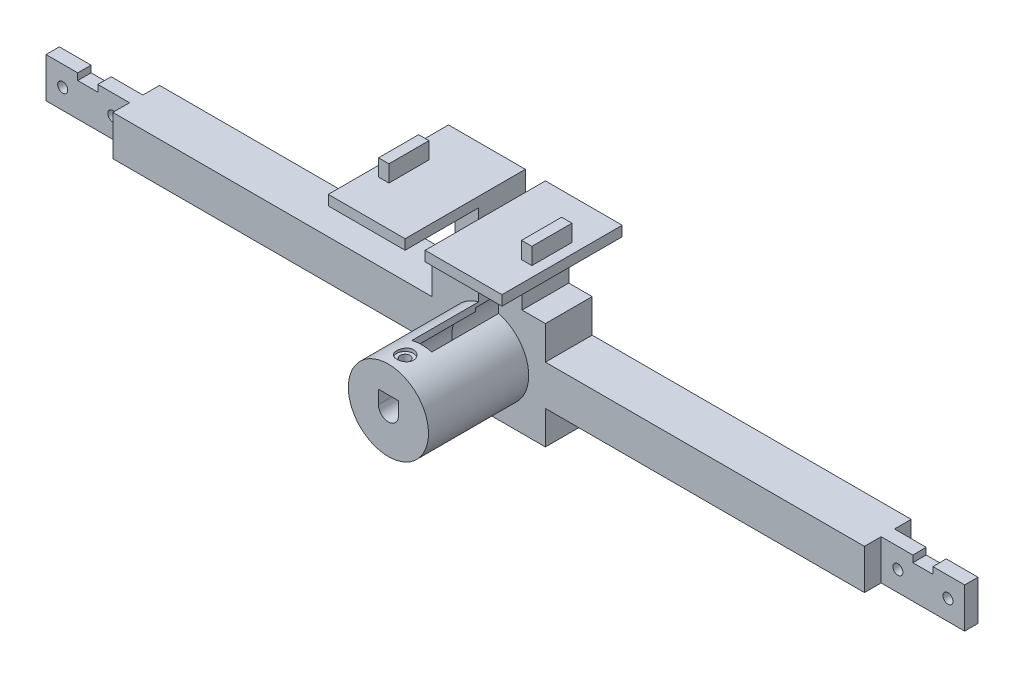
SolidWorks part; units mm, degrees
other "Markup1"
sketch "Sketch20" plane through (-137.5, 44, 54) normal (-0.9322, 0.081, 0.3528) x (0.3588, 0.0788, 0.9301)
material "PLA"
ref_plane "Front Plane" through (0, 0, 0) normal (0, 0, 1) x (1, 0, 0)
ref_plane "Top Plane" through (0, 0, 0) normal (0, 1, 0) x (1, 0, 0)
ref_plane "Right Plane" through (0, 0, 0) normal (1, 0, 0) x (0, 0, -1)
sketch "Sketch1" plane through (0, 0, 0) normal (0, 0, 1) x (1, 0, 0)
  line L0 (10, 16) -> (17, 16)
  line L1 (-17, -16) -> (17, -16)
  line L2 (-137.5, -6) -> (-137.5, 6)
  line L3 (-17, 16) -> (-10, 16)
  line L4 (137.5, -6) -> (137.5, 6)
  line L7 (-10, 36) -> (10, 36)
  line L8 (-10, 36) -> (-10, 16)
  line L10 (10, 36) -> (10, 16)
  line L11 (0, -55) -> (0, 55) construction
  line L14 (-137.5, 6) -> (-17, 6)
  line L15 (-17, 16) -> (-17, 6)
  line L16 (137.5, 6) -> (17, 6)
  line L17 (17, 16) -> (17, 6)
  line L20 (55, 0) -> (-55, 0) construction
  line L22 (17, -16) -> (17, -6)
  line L23 (137.5, -6) -> (17, -6)
  line L25 (-137.5, -6) -> (-17, -6)
  line L26 (-17, -16) -> (-17, -6)
  point P0 (0, 0)
  point P6 (0, 36)
  dimension "D1" = 275
  dimension "D2" = 12
  dimension "D3" = 20
  dimension "D4" = 20
  dimension "D5" = 7
  dimension "D6" = 10
extrude "Boss-Extrude1" add sketch "Sketch1" along normal blind 14 contours L3 L8 L7 L10 L0 L17 L16 L4 L23 L22 L1 L26 L25 L2 L14 L15
sketch "Sketch2" plane through (0, 0, 14) normal (0, 0, 1) x (1, 0, 0)
  circle A0 centre (0, 0) radius 12
  dimension "D1" = 24
extrude "Boss-Extrude2" add sketch "Sketch2" along normal blind 30 contours A0
sketch "Sketch5" plane through (0, 0, 0) normal (0, 0, -1) x (-1, 0, 0)
  line L2 (-3, 36) -> (-3, 10.583)
  line L4 (3, 36) -> (3, 10.583)
  line L6 (10, 36) -> (-10, 36) construction
  line L7 (-3, 36) -> (3, 36)
  arc A0 (-3, 10.583) -> (3, 10.583) centre (0, 0) ccw
  point P7 (0, 36)
  point P8 (0, 36)
  dimension "D1" = 22
  dimension "D2" = 6
extrude "Cut-Extrude2" cut sketch "Sketch5" against normal offset from surface (34 mm away) 10 contours A0 L4 L7 L2 up to face at (12, 0, 44)
sketch "Sketch7" plane through (0, 0, 34) normal (0, 0, -1) x (-1, 0, 0)
  line L0 (-3, 10.583) -> (-3, 9.5394)
  line L1 (3, 10.583) -> (3, 9.5394)
  arc A0 (-3, 9.5394) -> (3, 9.5394) centre (0, 0) ccw
  arc A1 (-3, 10.583) -> (3, 10.583) centre (0, 0) ccw construction
  arc A2 (-3, 10.583) -> (3, 10.583) centre (0, 0) ccw
  dimension "D1" = 1
extrude "Boss-Extrude3" add sketch "Sketch7" along normal offset from surface (19 mm away) 1 up to face at (0, 8.7809, 14)
sketch "Sketch6" plane through (0, 0, 44) normal (0, 0, 1) x (1, 0, 0)
  line L0 (-3, 0) -> (-3, 4)
  line L1 (-3, 4) -> (3, 4)
  line L2 (3, 4) -> (3, 0)
  arc A0 (-3, 0) -> (3, 0) centre (0, 0) ccw
  dimension "D1" = 6
  dimension "D2" = 4
extrude "Cut-Extrude3" cut sketch "Sketch6" against normal through all contours A0 L2 L1 L0
sketch "Sketch10" plane through (0, 4, 0) normal (0, -1, 0) x (-1, 0, 0)
  line L0 (-3, -44) -> (3, -34) construction
  circle A0 centre (0, -39) radius 1.5
  point P2 (0, -39)
  dimension "D1" = 3
extrude "Cut-Extrude5" cut sketch "Sketch10" against normal through all
sketch "Sketch11" plane through (0, 4, 0) normal (0, -1, 0) x (1, 0, 0)
  line L1 (2, 37.8453) -> (2, 40.1547)
  line L2 (2, 40.1547) -> (0, 41.3094)
  line L3 (0, 41.3094) -> (-2, 40.1547)
  line L4 (-2, 40.1547) -> (-2, 37.8453)
  line L5 (-2, 37.8453) -> (0, 36.6906)
  line L6 (0, 36.6906) -> (2, 37.8453)
  circle A0 centre (0, 39) radius 2 construction
  point P1 (1, 40.7321)
  dimension "D1" = 4
extrude "Cut-Extrude6" cut sketch "Sketch11" against normal blind 1.5
sketch "Sketch12" plane through (10, 0, 0) normal (1, 0, 0) x (0, 0, -1)
  line L0 (-14, 36) -> (0, 36) construction
  circle A0 centre (-7, 30.5) radius 1.5
  point P4 (-7, 36)
  dimension "D1" = 3
  dimension "D2" = 5.5
extrude "Cut-Extrude7" cut sketch "Sketch12" against normal up to surface (20 mm away) up to face at (-10, 26, 7)
sketch "Sketch13" plane through (10, 0, 0) normal (1, 0, 0) x (0, 0, -1)
  circle A0 centre (-7, 30.5) radius 2.5
  dimension "D1" = 5
extrude "Cut-Extrude8" cut sketch "Sketch13" against normal blind 1
sketch "Sketch14" plane through (-10, 0, 0) normal (-1, 0, 0) x (0, 0, 1)
  line L1 (4.6906, 30.5) -> (5.8453, 28.5)
  line L2 (5.8453, 28.5) -> (8.1547, 28.5)
  line L3 (8.1547, 28.5) -> (9.3094, 30.5)
  line L4 (9.3094, 30.5) -> (8.1547, 32.5)
  line L5 (8.1547, 32.5) -> (5.8453, 32.5)
  line L6 (5.8453, 32.5) -> (4.6906, 30.5)
  circle A0 centre (7, 30.5) radius 2 construction
  dimension "D1" = 4
extrude "Cut-Extrude9" cut sketch "Sketch14" against normal blind 1 contours L6 L1 L2 L3 L4 L5
sketch "Sketch15" plane through (0, 6, 0) normal (0, 1, 0) x (1, 0, 0)
  line L10 (-137.5, -14) -> (-112.5, -14)
  line L15 (-137.5, -14) -> (-137.5, -9)
  line L16 (-137.5, -9) -> (-112.5, -9)
  line L17 (-112.5, -14) -> (-112.5, -9)
  line L18 (-137.5, 0) -> (-112.5, 0)
  line L19 (-137.5, 0) -> (-137.5, -5)
  line L20 (-137.5, -5) -> (-112.5, -5)
  line L21 (-112.5, 0) -> (-112.5, -5)
  dimension "D1" = 25
  dimension "D2" = 5
  dimension "D3" = 5
  dimension "D4" = 25
extrude "Cut-Extrude11" cut sketch "Sketch15" against normal through all
mirror "Mirror2" about plane through (0, 0, 0) normal (1, 0, 0) of "Cut-Extrude11"
sketch "Sketch17" plane through (0, 5.5, 0) normal (0, -1, 0) x (1, 0, 0)
  circle A0 centre (0, 39) radius 2.5
  dimension "D1" = 5
extrude "Cut-Extrude12" cut sketch "Sketch17" against normal through all from offset 5.5 offset against normal yes
sketch "Sketch18" plane through (0, 36, 0) normal (0, 1, 0) x (1, 0, 0)
  line L0 (-17, 0) -> (-10, 0) construction
  line L1 (-26, 0) -> (-3, 0)
  line L2 (-26, 0) -> (-26, -36)
  line L3 (-26, -36) -> (-3, -36)
  line L4 (26, 0) -> (26, -36)
  line L5 (3, -14) -> (3, -34) construction
  line L7 (-3, 0) -> (-3, -36)
  line L9 (3, 0) -> (3, -36)
  line L10 (3, 0) -> (26, 0)
  line L11 (3, -36) -> (26, -36)
  dimension "D1" = 36
  dimension "D2" = 52
extrude "Boss-Extrude7" add sketch "Sketch18" along normal blind 3
sketch "Sketch19" plane through (0, 39, 0) normal (0, 1, 0) x (1, 0, 0)
  line L0 (-26, 0) -> (-26, -36) construction
  line L1 (-22.95, -12) -> (-19.85, -12)
  line L2 (-22.95, -12) -> (-22.95, -24)
  line L3 (-22.95, -24) -> (-19.85, -24)
  line L4 (-19.85, -12) -> (-19.85, -24)
  line L5 (-22.95, -12) -> (-19.85, -24) construction
  line L6 (-22.95, -24) -> (-19.85, -12) construction
  line L7 (0, -24.2) -> (0, 24.2) construction
  line L8 (22.95, -24) -> (19.85, -12) construction
  line L9 (22.95, -12) -> (19.85, -24) construction
  line L10 (19.85, -12) -> (19.85, -24)
  line L11 (22.95, -24) -> (19.85, -24)
  line L12 (22.95, -12) -> (22.95, -24)
  line L13 (22.95, -12) -> (19.85, -12)
  point P0 (-21.4, -18)
  point P7 (-26, -18)
  point P8 (-21.4, -24)
  point P16 (21.4, -18)
  dimension "D1" = 3.1
  dimension "D2" = 12
  dimension "D3" = 21.4
extrude "Boss-Extrude8" add sketch "Sketch19" along normal blind 5
sketch "Sketch21" plane through (0, 0, 9) normal (0, 0, 1) x (1, 0, 0)
  line L0 (-137.5, -6) -> (-137.5, 6) construction
  line L1 (-112.5, -6) -> (-112.5, 6) construction
  line L2 (-112.5, 6) -> (-137.5, 6) construction
  line L4 (-128, 6) -> (-128, 4)
  line L5 (-128, 4) -> (-122, 4)
  line L6 (-122, 6) -> (-122, 4)
  line L7 (-125, 6) -> (-122, 4) construction
  line L8 (-128, 4) -> (-125, 6) construction
  line L9 (-128, 6) -> (-122, 6)
  circle A0 centre (-132.5, 0) radius 1.5
  circle A1 centre (-117.5, 0) radius 1.5
  point P5 (-137.5, 0)
  point P10 (-125, 6)
  point P12 (-125, 6)
  dimension "D1" = 3
  dimension "D3" = 2
  dimension "D2" = 5
  dimension "D4" = 5
  dimension "D5" = 6
extrude "Cut-Extrude13" cut sketch "Sketch21" against normal through all
mirror "Mirror3" about plane through (0, 0, 0) normal (1, 0, 0) of "Cut-Extrude13"
